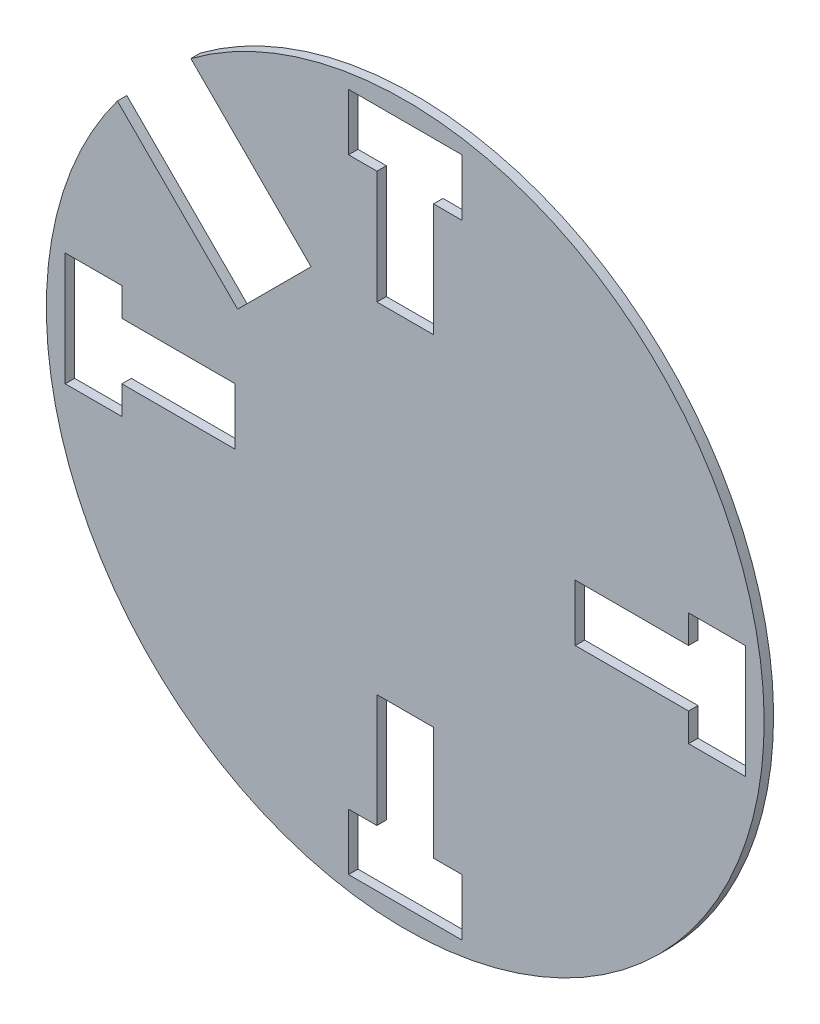
SolidWorks part; units mm, degrees
ref_plane "Plan de face" through (0, 0, 0) normal (0, 0, 1) x (1, 0, 0)
ref_plane "Plan de dessus" through (0, 0, 0) normal (0, 1, 0) x (1, 0, 0)
ref_plane "Plan de droite" through (0, 0, 0) normal (1, 0, 0) x (0, 0, -1)
sketch "Esquisse1" plane through (0, 0, 0) normal (0, 0, 1) x (1, 0, 0)
  circle A0 centre (0, 0) radius 190
  dimension "D1" = 380
extrude "Boss.-Extru.1" add sketch "Esquisse1" against normal blind 5
sketch "Esquisse2" plane through (0, 0, 0) normal (0, 0, 1) x (1, 0, 0)
  line L4 (-15, 150) -> (-15, 90)
  line L5 (0, 190) -> (0, -190) construction
  line L6 (-190, 0) -> (190, 0) construction
  line L7 (-30, 180) -> (30, 180)
  line L8 (-30, 180) -> (-30, 150)
  line L10 (30, 180) -> (30, 150)
  line L11 (-15, 90) -> (15, 90)
  line L12 (15, 90) -> (15, 150)
  line L13 (-15, 150) -> (-30, 150)
  line L14 (30, 150) -> (15, 150)
  line L15 (30, -180) -> (30, -150)
  line L16 (-30, -180) -> (30, -180)
  line L17 (-30, -180) -> (-30, -150)
  line L18 (-15, -150) -> (-30, -150)
  line L19 (-15, -150) -> (-15, -90)
  line L20 (-15, -90) -> (15, -90)
  line L21 (15, -90) -> (15, -150)
  line L22 (30, -150) -> (15, -150)
  line L23 (0, 0) -> (134.3503, 134.3503) construction
  line L24 (180, 30) -> (150, 30)
  line L25 (180, -30) -> (180, 30)
  line L26 (180, -30) -> (150, -30)
  line L27 (150, -15) -> (150, -30)
  line L28 (150, -15) -> (90, -15)
  line L29 (90, -15) -> (90, 15)
  line L30 (90, 15) -> (150, 15)
  line L31 (150, 30) -> (150, 15)
  line L32 (0, 0) -> (-134.3503, 134.3503) construction
  line L33 (-180, -30) -> (-150, -30)
  line L34 (-180, 30) -> (-180, -30)
  line L35 (-180, 30) -> (-150, 30)
  line L36 (-150, 15) -> (-150, 30)
  line L37 (-150, 15) -> (-90, 15)
  line L38 (-90, 15) -> (-90, -15)
  line L39 (-90, -15) -> (-150, -15)
  line L40 (-150, -30) -> (-150, -15)
  circle A0 centre (0, 0) radius 190 construction
  point P13 (0, 90)
  dimension "D1" = 30
  dimension "D2" = 60
  dimension "D3" = 60
  dimension "D4" = 30
  dimension "D5" = 150
  dimension "D6" = 180
  dimension "D7" = 45
extrude "Enlèv. mat.-Extru.1" cut sketch "Esquisse2" against normal blind 5
sketch "Esquisse3" plane through (0, 0, 0) normal (0, 0, 1) x (1, 0, 0)
  line L0 (-134.3503, 134.3503) -> (134.3503, -134.3503) construction
  line L5 (0, 190) -> (0, -190) construction
  line L6 (-88.7414, 49.8506) -> (-49.8506, 88.7414)
  line L8 (-120.5612, 159.4521) -> (-159.4521, 120.5612)
  line L10 (-159.4521, 120.5612) -> (-152.381, 113.4902)
  line L11 (-152.381, 113.4902) -> (-88.7414, 49.8506)
  line L12 (-120.5612, 159.4521) -> (-113.4902, 152.381)
  line L13 (-113.4902, 152.381) -> (-49.8506, 88.7414)
  circle A1 centre (0, 0) radius 190 construction
  point P11 (-69.296, 69.296)
  point P17 (-140.0067, 140.0067)
  dimension "D1" = 45
  dimension "D2" = 55
  dimension "D3" = 10
  dimension "D4" = 90
extrude "Enlèv. mat.-Extru.2" cut sketch "Esquisse3" against normal blind 10
